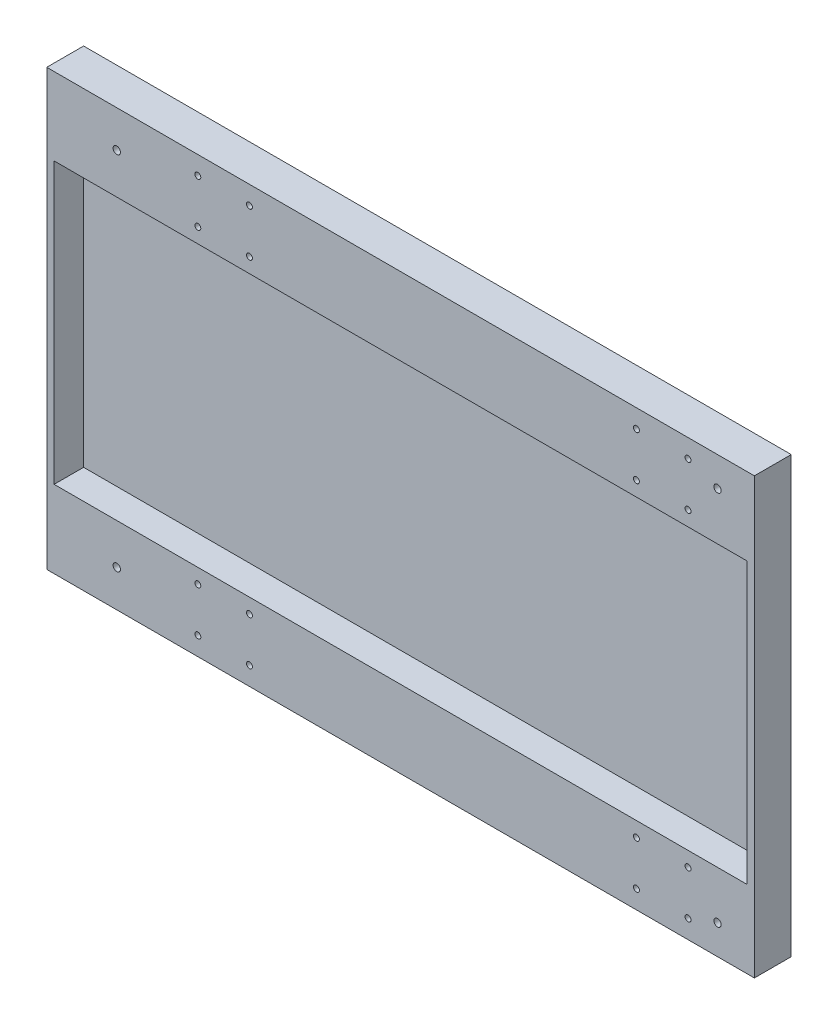
SolidWorks part; units mm, degrees
ref_plane "Front Plane" through (0, 0, 0) normal (0, 0, 1) x (1, 0, 0)
ref_plane "Top Plane" through (0, 0, 0) normal (0, 1, 0) x (1, 0, 0)
ref_plane "Right Plane" through (0, 0, 0) normal (1, 0, 0) x (0, 0, -1)
sketch "Sketch1" plane through (0, 0, 0) normal (0, 0, 1) x (1, 0, 0)
  line L1 (-609.6, -374.65) -> (609.6, -374.65)
  line L2 (-609.6, -374.65) -> (-609.6, 374.65)
  line L3 (-609.6, 374.65) -> (609.6, 374.65)
  line L4 (609.6, -374.65) -> (609.6, 374.65)
  line L5 (-609.6, -374.65) -> (609.6, 374.65) construction
  line L6 (-609.6, 374.65) -> (609.6, -374.65) construction
  point P0 (0, 0)
  dimension "D1" = 1219.2
  dimension "D2" = 749.3
extrude "Boss-Extrude1" add sketch "Sketch1" along normal blind 12.7
sketch "Sketch2" plane through (0, 0, 12.7) normal (0, 0, 1) x (1, 0, 0)
  line L0 (-609.6, 374.65) -> (-609.6, -374.65) construction
  line L1 (-609.6, 374.65) -> (609.6, 374.65)
  line L2 (-609.6, 374.65) -> (-609.6, 241.3)
  line L3 (-609.6, 241.3) -> (609.6, 241.3)
  line L4 (609.6, 374.65) -> (609.6, 241.3)
  line L5 (609.6, 374.65) -> (-609.6, 374.65) construction
  line L7 (-609.6, 0) -> (716.7187, 0) construction
  line L8 (-609.6, -241.3) -> (609.6, -241.3)
  line L9 (609.6, -374.65) -> (609.6, -241.3)
  line L10 (-609.6, -374.65) -> (609.6, -374.65)
  line L11 (-609.6, -374.65) -> (-609.6, -241.3)
  line L12 (-596.9, 241.3) -> (-596.9, -241.3)
  line L13 (596.9, 241.3) -> (596.9, -241.3)
  line L14 (-609.6, 241.3) -> (-609.6, -241.3)
  line L15 (609.6, -241.3) -> (609.6, 241.3)
  line L16 (609.6, -374.65) -> (609.6, 374.65) construction
  line L17 (393.7, 254) -> (508, 254)
  line L18 (-361.95, 254) -> (-247.65, 254)
  line L19 (-361.95, 254) -> (-361.95, 355.6)
  line L20 (-361.95, 355.6) -> (-247.65, 355.6)
  line L21 (-247.65, 254) -> (-247.65, 355.6)
  line L22 (-361.95, 254) -> (-247.65, 355.6) construction
  line L23 (-361.95, 355.6) -> (-247.65, 254) construction
  line L24 (393.7, 254) -> (393.7, 355.6)
  line L25 (393.7, 355.6) -> (508, 355.6)
  line L26 (508, 254) -> (508, 355.6)
  line L27 (393.7, 254) -> (508, 355.6) construction
  line L28 (393.7, 355.6) -> (508, 254) construction
  circle A0 centre (-349.25, 342.9) radius 5.08
  circle A1 centre (-260.35, 342.9) radius 5.08
  circle A2 centre (-260.35, 266.7) radius 5.08
  circle A3 centre (-349.25, 266.7) radius 5.08
  circle A4 centre (406.4, 342.9) radius 5.08
  circle A5 centre (495.3, 342.9) radius 5.08
  circle A6 centre (495.3, 266.7) radius 5.08
  circle A7 centre (406.4, 266.7) radius 5.08
  circle A8 centre (406.4, -266.7) radius 5.08
  circle A9 centre (495.3, -266.7) radius 5.08
  circle A10 centre (495.3, -342.9) radius 5.08
  circle A11 centre (406.4, -342.9) radius 5.08
  circle A12 centre (-349.25, -342.9) radius 5.08
  circle A13 centre (-349.25, -266.7) radius 5.08
  circle A14 centre (-260.35, -342.9) radius 5.08
  circle A15 centre (-260.35, -266.7) radius 5.08
  point P8 (-304.8, 304.8)
  point P33 (0, 0)
  point P34 (0, 0)
  point P35 (0, 0)
  point P36 (-403.3016, 354.1552)
  point P37 (-374.7502, 307.6319)
  point P38 (-312.7646, 276.9067)
  point P39 (450.85, 304.8)
  line M6 (609.6, -374.65) -> (609.6, 374.65)
  line M7 (609.6, 374.65) -> (-609.6, 374.65)
  line M8 (-609.6, 374.65) -> (-609.6, -374.65)
  line M9 (-609.6, -374.65) -> (609.6, -374.65)
  dimension "D6" = 10.16
  dimension "D13" = 10.16
  dimension "D1" = 133.35
  dimension "D2" = 12.7
  dimension "D3" = 12.7
  dimension "D4" = 114.3
  dimension "D5" = 101.6
  dimension "D7" = 76.2
  dimension "D8" = 88.9
  dimension "D9" = 12.7
  dimension "D10" = 12.7
  dimension "D11" = 247.65
  dimension "D12" = 19.05
  dimension "D14" = 76.2
  dimension "D15" = 88.9
  dimension "D16" = 12.7
  dimension "D17" = 12.7
  dimension "D18" = 101.6
  dimension "D19" = 114.3
  dimension "D20" = 19.05
  dimension "D21" = 101.6
extrude "Boss-Extrude2" add sketch "Sketch2" along normal blind 50.8 contours L7 L12 L3 M8 | L17 L26 L25 L24 A7 A6 A5 A4 | L18 L21 L20 L19 A3 A2 A1 A0 | L3 L26 L17 L24 L25 L21 L18 L19 L20 M8 M6 M7 | L8 M8 M9 M6 | L3 L13 L8 M6
sketch "Sketch3" plane through (0, 0, 63.5) normal (0, 0, 1) x (1, 0, 0)
  line L0 (-609.6, 374.65) -> (-609.6, -374.65) construction
  line L1 (609.6, 374.65) -> (-609.6, 374.65) construction
  line L2 (609.6, -374.65) -> (609.6, 374.65) construction
  line L3 (-609.6, 0) -> (596.9, 0) construction
  line L4 (596.9, 241.3) -> (596.9, -241.3) construction
  circle A0 centre (-488.95, 311.15) radius 6.35
  circle A1 centre (546.1, 323.85) radius 6.35
  circle A2 centre (546.1, -323.85) radius 6.35
  circle A3 centre (-488.95, -311.15) radius 6.35
  dimension "D1" = 12.7
  dimension "D2" = 120.65
  dimension "D3" = 63.5
  dimension "D4" = 12.7
  dimension "D5" = 63.5
  dimension "D6" = 50.8
extrude "Cut-Extrude1" cut sketch "Sketch3" against normal through all
